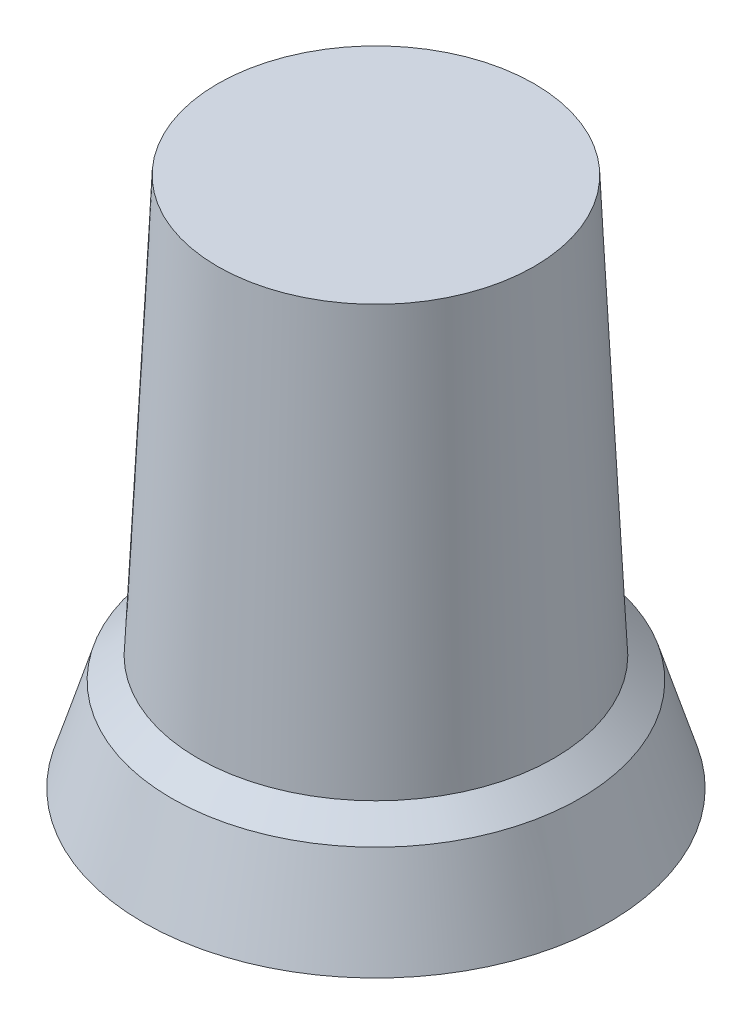
SolidWorks part; units mm, degrees
ref_plane "Piano frontale" through (0, 0, 0) normal (0, 0, 1) x (1, 0, 0)
ref_plane "Piano superiore" through (0, 0, 0) normal (0, 1, 0) x (1, 0, 0)
ref_plane "Piano destro" through (0, 0, 0) normal (1, 0, 0) x (0, 0, -1)
ref_axis "Assi1" through (0, 55, 0) along (0, -1, 0)
sketch "Schizzo1" plane through (0, 0, 0) normal (0, 0, 1) x (1, 0, 0)
  line L0 (6.8307, -8.3873) -> (5.9725, -5.587)
  line L1 (7.5, -8.1822) -> (6.5806, -5.1822)
  line L2 (6.5806, -5.1822) -> (5.7381, -4.4822)
  line L3 (5.7381, -4.4822) -> (5.1, 8.9178)
  line L4 (5.1, 8.9178) -> (0, 8.9178)
  line L5 (0, 55) -> (0, -55) construction
  line L6 (5.9725, -5.587) -> (5.0536, -4.8235)
  line L7 (5.0536, -4.8235) -> (4.4325, 8.2178)
  line L8 (4.4325, 8.2178) -> (0, 8.2178)
  line L9 (7.5, -8.1822) -> (6.8307, -8.3873)
  line L10 (0, 8.2178) -> (0, 8.9178)
  point P0 (0, 0)
  dimension "D1" = 5.1
  dimension "D2" = 7.5
  dimension "D3" = 17.1
  dimension "D4" = 3
  dimension "D5" = 0.7
  dimension "D6" = 0.7
revolve "Rivoluzione1" add sketch "Schizzo1" angle 360 about axis through (0, 55, 0) along (0, -1, 0)
